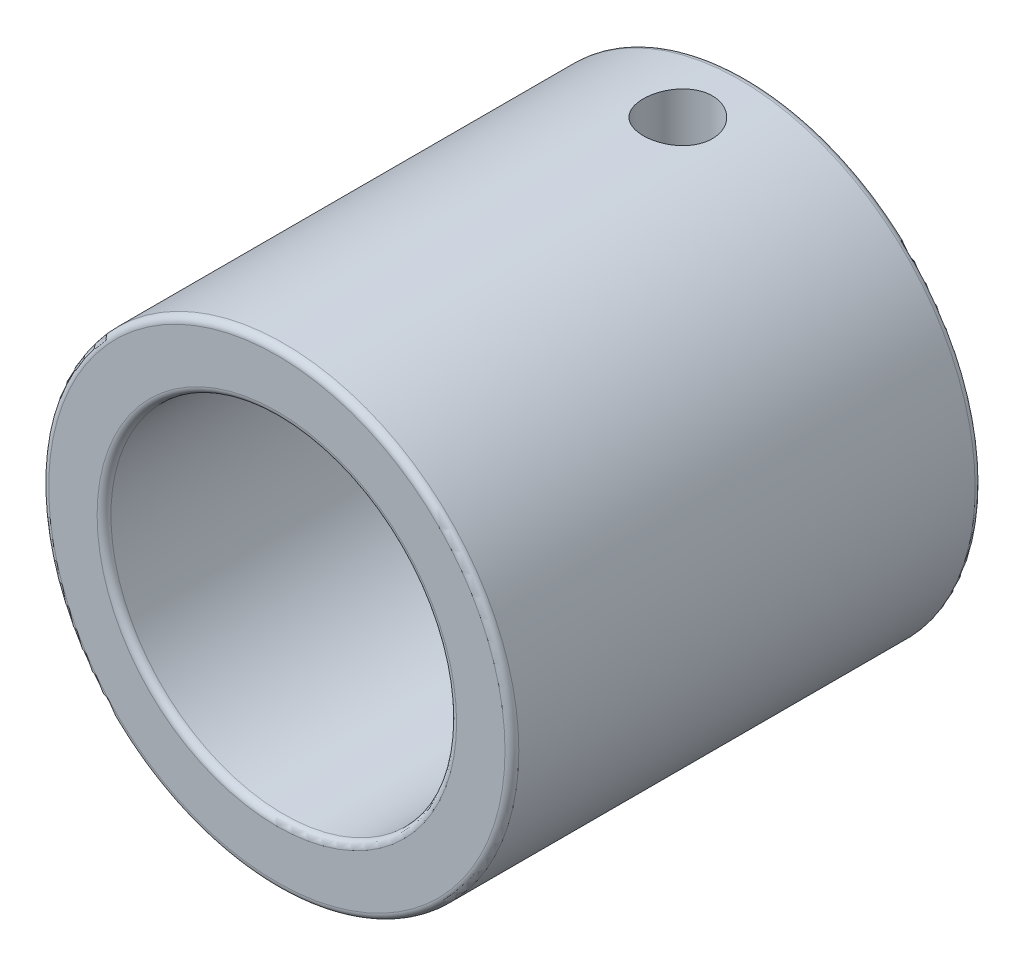
SolidWorks part; units mm, degrees
ref_plane "Ön Düzlem" through (0, 0, 0) normal (0, 0, 1) x (1, 0, 0)
ref_plane "Üst Düzlem" through (0, 0, 0) normal (0, 1, 0) x (1, 0, 0)
ref_plane "Sağ Düzlem" through (0, 0, 0) normal (1, 0, 0) x (0, 0, -1)
sketch "Çizim1" plane through (0, 0, 0) normal (0, 0, 1) x (1, 0, 0)
  circle A0 centre (0, 0) radius 17
  circle A1 centre (0, 0) radius 12.5
  dimension "D1" = 34
  dimension "D2" = 25
extrude "Yükseklik-Ekstrüzyon1" add sketch "Çizim1" along normal blind 34
fillet "Radyus1" radius 0.5 4 edges at (12.5, 0, 0) (17, 0, 0) (12.5, 0, 34) (17, 0, 34)
sketch "Çizim2" plane through (0, 0, 0) normal (0, 1, 0) x (1, 0, 0)
  circle A0 centre (0, -5) radius 2.5
  dimension "D1" = 5
  dimension "D2" = 5
extrude "Kes-Ekstrüzyon1" cut sketch "Çizim2" against normal through all both and the other way through all
